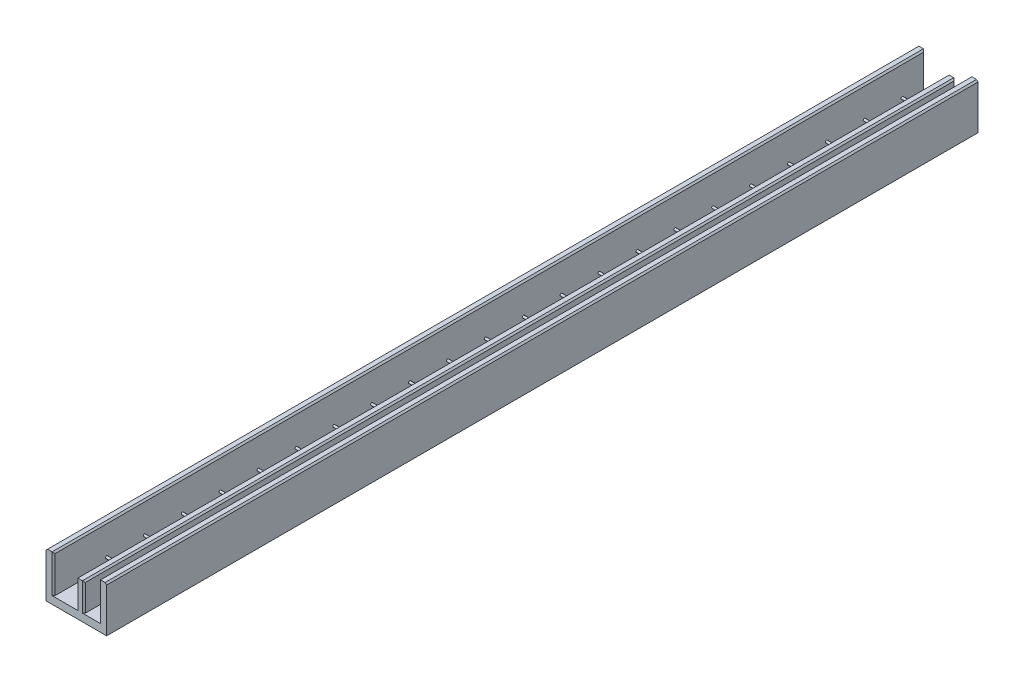
SolidWorks part; units mm, degrees
ref_plane "Alzado" through (0, 0, 0) normal (0, 0, 1) x (1, 0, 0)
ref_plane "Planta" through (0, 0, 0) normal (0, 1, 0) x (1, 0, 0)
ref_plane "Vista lateral" through (0, 0, 0) normal (1, 0, 0) x (0, 0, -1)
sketch "Croquis1" plane through (0, 0, 0) normal (0, 0, 1) x (1, 0, 0)
  line L0 (0, 0) -> (-800, 0)
  line L1 (-800, 0) -> (-800, 600)
  line L2 (-800, 600) -> (-700, 600)
  line L3 (-700, 600) -> (-700, 100)
  line L4 (-700, 100) -> (-400, 100)
  line L5 (-400, 100) -> (-400, 470)
  line L6 (-400, 470) -> (-300, 470)
  line L7 (-300, 470) -> (-300, 100)
  line L8 (-300, 100) -> (-100, 100)
  line L9 (-100, 100) -> (-100, 600)
  line L10 (-100, 600) -> (0, 600)
  line L11 (0, 600) -> (0, 0)
  dimension "D1" = 800
  dimension "D2" = 600
  dimension "D3" = 100
  dimension "D4" = 500
  dimension "D5" = 300
  dimension "D6" = 370
  dimension "D7" = 100
  dimension "D8" = 370
  dimension "D9" = 200
extrude "Saliente-Extruir1" add sketch "Croquis1" along normal blind 11500
chamfer "Chaflán2" distance 20 angle 45 14 edges at (-100, 350, 0) (0, 600, 5750) (-700, 350, 0) (-700, 600, 5750) (-700, 350, 11500) (-100, 350, 11500) (-300, 285, 0) (-300, 285, 11500) (-300, 470, 5750) (-400, 285, 0) (-400, 285, 11500) (-400, 470, 5750) (-800, 600, 5750) (-100, 600, 5750)
sketch "Croquis2" plane through (-800, 0, 0) normal (-1, 0, 0) x (0, 0, 1)
  line L0 (0, 580) -> (0, 0) construction
  circle A0 centre (300, 200) radius 15
  dimension "D3" = 30
  dimension "D1" = 300
extrude "Saliente-Extruir2" add sketch "Croquis2" against normal up to surface (700 mm away) up to face at (-100, 340, 5750)
pattern_linear "MatrizL1" count 22 spacing 500 along (0, 0, 1) of "Saliente-Extruir2"
